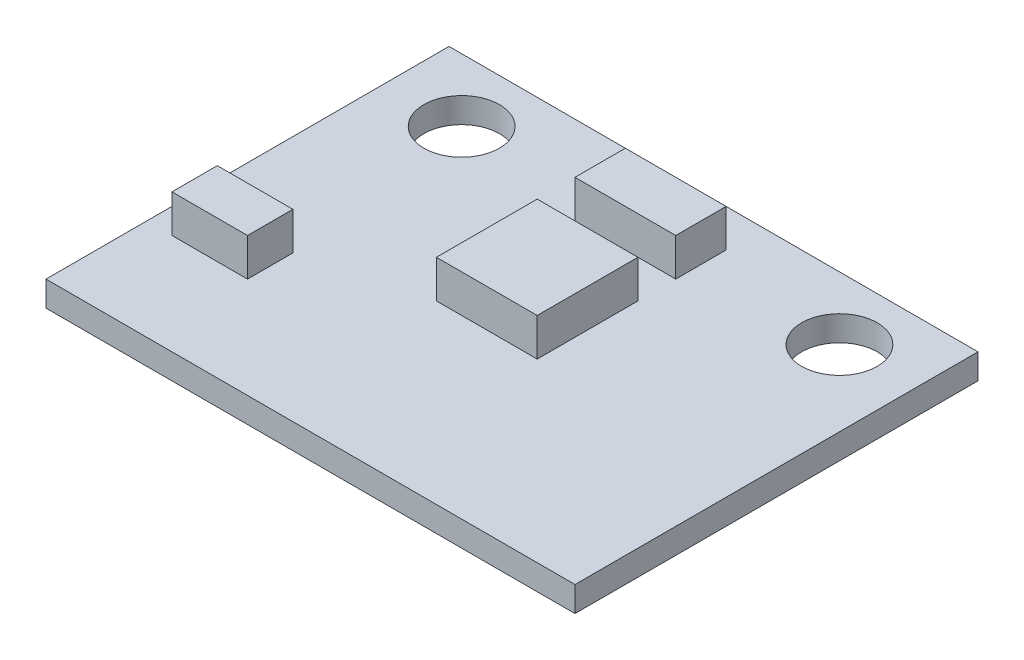
SolidWorks part; units mm, degrees
ref_plane "Front Plane" through (0, 0, 0) normal (0, 0, 1) x (1, 0, 0)
ref_plane "Top Plane" through (0, 0, 0) normal (0, 1, 0) x (1, 0, 0)
ref_plane "Right Plane" through (0, 0, 0) normal (1, 0, 0) x (0, 0, -1)
sketch "Sketch1" plane through (0, 0, 0) normal (0, 1, 0) x (1, 0, 0)
  line L0 (-7.5, 5.5) -> (7.5, 5.5) construction
  line L1 (-10.5, 8) -> (10.5, 8)
  line L2 (-10.5, 8) -> (-10.5, -8)
  line L3 (-10.5, -8) -> (10.5, -8)
  line L4 (10.5, 8) -> (10.5, -8)
  line L5 (-10.5, 8) -> (10.5, -8) construction
  line L6 (-10.5, -8) -> (10.5, 8) construction
  circle A0 centre (-7.5, 5.5) radius 1.5
  circle A1 centre (7.5, 5.5) radius 1.5
  point P0 (0, 0)
  point P10 (0, 5.5)
  dimension "D3" = 3
  dimension "D4" = 2.5
  dimension "D5" = 15
  dimension "D1" = 21
  dimension "D2" = 16
extrude "PCB" add sketch "Sketch1" along normal blind 1
sketch "Sketch2" plane through (0, 1, 0) normal (0, 1, 0) x (1, 0, 0)
  line L0 (-10.5, 8) -> (-10.5, -8) construction
  line L1 (-2, 3) -> (2, 3)
  line L2 (-2, 3) -> (-2, -1)
  line L3 (-2, -1) -> (2, -1)
  line L4 (2, 3) -> (2, -1)
  line L5 (-2, 3) -> (2, -1) construction
  line L6 (-2, -1) -> (2, 3) construction
  line L7 (-9.5, -2.2) -> (-6.5, -2.2)
  line L8 (-9.5, -2.2) -> (-9.5, -4)
  line L9 (-9.5, -4) -> (-6.5, -4)
  line L10 (-6.5, -2.2) -> (-6.5, -4)
  line L11 (-10.5, -8) -> (10.5, -8) construction
  point P0 (0, 1)
  dimension "D1" = 4
  dimension "D2" = 1
  dimension "D3" = 3
  dimension "D4" = 1.8
  dimension "D5" = 1
  dimension "D6" = 4
extrude "Components" add sketch "Sketch2" along normal blind 1.5
sketch "Sketch3" plane through (0, 1, 0) normal (0, 1, 0) x (1, 0, 0)
  line L0 (-2, 3) -> (-2, -1) construction
  line L1 (-2, 6.5) -> (2, 6.5)
  line L2 (-2, 6.5) -> (-2, 4.5)
  line L3 (-2, 4.5) -> (2, 4.5)
  line L4 (2, 6.5) -> (2, 4.5)
  line L5 (2, 3) -> (-2, 3) construction
  dimension "D1" = 4
  dimension "D2" = 2
  dimension "D3" = 1.5
extrude "Capacitor" add sketch "Sketch3" along normal blind 1.5
